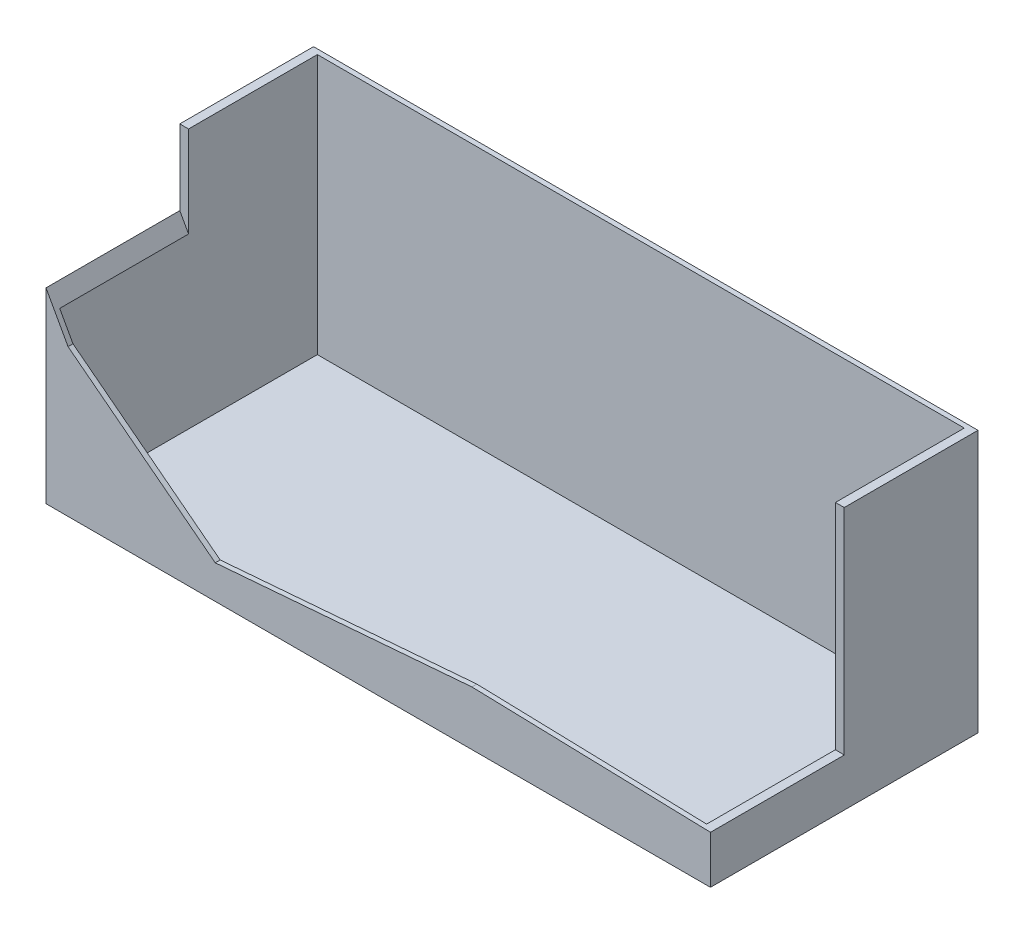
SolidWorks part; units mm, degrees
ref_plane "Front Plane" through (0, 0, 0) normal (0, 0, 1) x (1, 0, 0)
ref_plane "Top Plane" through (0, 0, 0) normal (0, 1, 0) x (1, 0, 0)
ref_plane "Right Plane" through (0, 0, 0) normal (1, 0, 0) x (0, 0, -1)
sketch "Sketch1" plane through (0, 0, 0) normal (0, 1, 0) x (1, 0, 0)
  line L1 (-3030, -1220) -> (3030, -1220)
  line L2 (2950, 1175) -> (-2950, 1175)
  line L3 (2950, 1175) -> (2950, -1175)
  line L4 (2950, -1175) -> (-2950, -1175)
  line L5 (-2950, 1175) -> (-2950, -1175)
  line L6 (2950, 1175) -> (-2950, -1175) construction
  line L7 (2950, -1175) -> (-2950, 1175) construction
  line L8 (-3030, -1220) -> (-3030, 1220)
  line L9 (-3030, 1220) -> (3030, 1220)
  line L10 (3030, -1220) -> (3030, 1220)
  line L11 (-3030, -1220) -> (3030, 1220) construction
  line L12 (-3030, 1220) -> (3030, -1220) construction
  point P0 (0, 0)
  point P1 (0, 0)
  dimension "D1" = 2350
  dimension "D2" = 5900
  dimension "D3" = 6060
  dimension "D4" = 2440
extrude "Boss-Extrude1" add sketch "Sketch1" along normal blind 2390
sketch "Sketch2" plane through (0, 0, 0) normal (0, 0, 1) x (1, 0, 0)
  line L0 (-2829.0661, 1341.2503) -> (-1486.3847, 305.0174)
  line L1 (-1486.3847, 305.0174) -> (854.001, 495.0202)
  line L2 (854.001, 495.0202) -> (4288.4123, 400.0188)
  line L3 (4288.4123, 400.0188) -> (4288.4123, 2458.6053)
  line L4 (4288.4123, 2458.6053) -> (-3446.1575, 2458.6053)
  line L5 (-3446.1575, 2458.6053) -> (-2829.0661, 1341.2503)
extrude "Cut-Extrude1" cut sketch "Sketch2" along normal through all
sketch "Sketch3" plane through (0, 0, 0) normal (0, -1, 0) x (1, 0, 0)
  line L0 (3030, 1220) -> (3030, -1220) construction
  line L1 (3030, -1220) -> (-3030, -1220) construction
  line L2 (-3030, -1220) -> (-3030, 1220) construction
  line L3 (-3030, 1220) -> (3030, 1220) construction
  line L4 (3030, 1220) -> (3030, -1220)
  line L5 (3030, -1220) -> (-3030, -1220)
  line L6 (-3030, -1220) -> (-3030, 1220)
  line L7 (-3030, 1220) -> (3030, 1220)
extrude "Boss-Extrude2" add sketch "Sketch3" against normal blind 20
